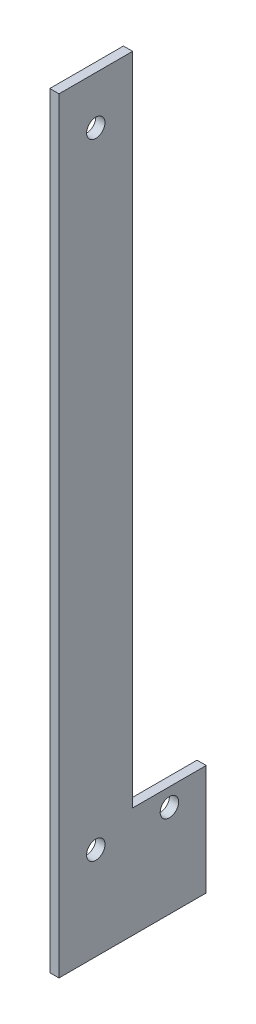
SolidWorks part; units mm, degrees
ref_plane "Front Plane" through (0, 0, 0) normal (0, 0, 1) x (1, 0, 0)
ref_plane "Top Plane" through (0, 0, 0) normal (0, 1, 0) x (1, 0, 0)
ref_plane "Right Plane" through (0, 0, 0) normal (1, 0, 0) x (0, 0, -1)
sketch "Sketch1" plane through (0, 0, 0) normal (1, 0, 0) x (0, 0, -1)
  line L1 (0, 0) -> (25.4, 0)
  line L2 (0, 0) -> (0, 264.16)
  line L3 (0, 264.16) -> (25.4, 264.16)
  line L4 (25.4, 38.1) -> (25.4, 264.16)
  line L5 (25.4, 0) -> (50.8, 0)
  line L7 (25.4, 38.1) -> (50.8, 38.1)
  line L8 (50.8, 0) -> (50.8, 38.1)
extrude "Boss-Extrude1" add sketch "Sketch1" along normal blind 3.175 contours L4 L3 L2 L1 L5 L8 L7
sketch "Sketch2" plane through (3.175, 0, 0) normal (1, 0, 0) x (0, 0, -1)
  circle A0 centre (12.7, 247.65) radius 3.175
  circle A1 centre (38.1, 32) radius 3.175
  circle A2 centre (12.7, 32) radius 3.175
  point P10 (0, 0)
  point P11 (12.7, 32)
extrude "Cut-Extrude1" cut sketch "Sketch2" against normal blind 3.175
